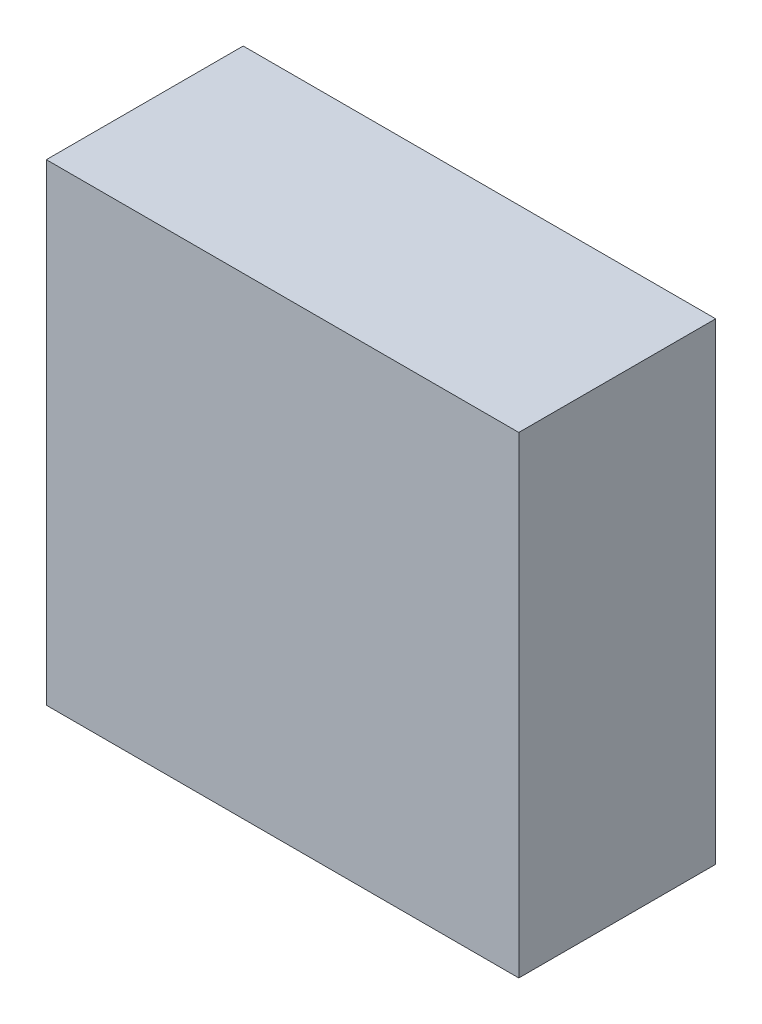
SolidWorks part; units mm, degrees
ref_plane "Front Plane" through (0, 0, 0) normal (0, 0, 1) x (1, 0, 0)
ref_plane "Top Plane" through (0, 0, 0) normal (0, 1, 0) x (1, 0, 0)
ref_plane "Right Plane" through (0, 0, 0) normal (1, 0, 0) x (0, 0, -1)
sketch "Sketch1" plane through (0, 0, 0) normal (0, 0, 1) x (1, 0, 0)
  line L1 (6, 6) -> (-6, 6)
  line L2 (6, 6) -> (6, -6)
  line L3 (6, -6) -> (-6, -6)
  line L4 (-6, 6) -> (-6, -6)
  dimension "D1" = 6
  dimension "D2" = 12
  dimension "D3" = 12
  dimension "D4" = 6
extrude "Boss-Extrude1" add sketch "Sketch1" along normal blind 5
